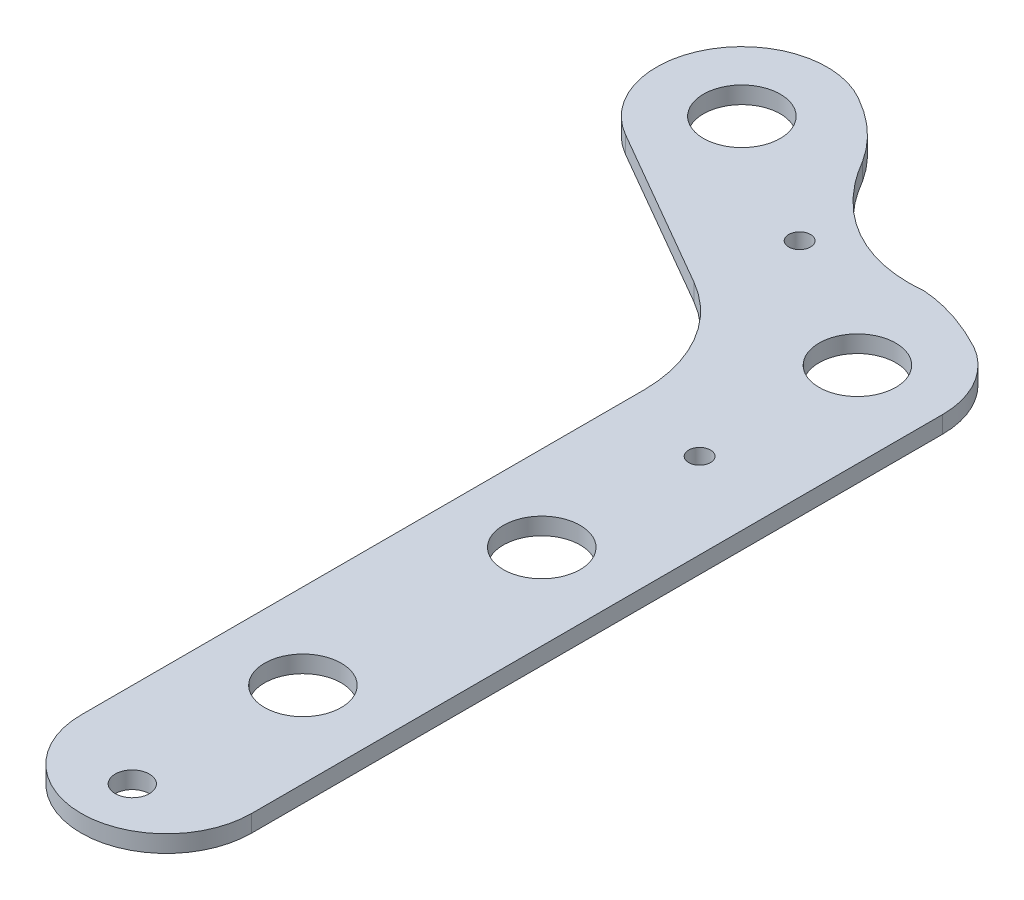
SolidWorks part; units mm, degrees
material "PC High Viscosity"
ref_plane "Front Plane" through (0, 0, 0) normal (0, 0, 1) x (1, 0, 0)
ref_plane "Top Plane" through (0, 0, 0) normal (0, 1, 0) x (1, 0, 0)
ref_plane "Right Plane" through (0, 0, 0) normal (1, 0, 0) x (0, 0, -1)
sketch "Sketch2" plane through (0, 0, 0) normal (0, 1, 0) x (1, 0, 0)
  line L0 (0, 117.475) -> (0, -88.9) construction
  line L1 (0, 117.475) -> (-101.7363, 176.2125) construction
  line L2 (31.75, -78.393) -> (31.75, 117.475)
  line L3 (-31.75, -18.2729) -> (-31.75, 69.8147)
  line L4 (-57.15, 113.8088) -> (-117.6113, 148.7162)
  line L5 (-59.6527, 249.1035) -> (-151.7481, 89.5896) construction
  line L6 (-85.8613, 203.7088) -> (15.875, 144.9713) construction
  line L7 (59.941, 221.2959) -> (-45.6102, 38.4758) construction
  line L8 (-50.8682, 146.8437) -> (-34.9932, 174.3401) construction
  line L9 (-34.9932, 174.3401) -> (22.7698, 274.3885) construction
  line L10 (-31.75, -139.7) -> (-31.75, -18.2729)
  line L11 (31.75, -78.393) -> (31.75, -139.7)
  circle A0 centre (0, 0) radius 14.2875
  circle A1 centre (0, -88.9) radius 14.2875
  circle A2 centre (0, 117.475) radius 14.2875
  circle A3 centre (-101.7363, 176.2125) radius 14.2875
  arc A5 (-117.6113, 148.7162) -> (-85.8613, 203.7088) centre (-101.7363, 176.2125) cw
  arc A6 (31.75, 117.475) -> (15.875, 144.9713) centre (0, 117.475) ccw
  arc A7 (-31.75, 69.8147) -> (-57.15, 113.8088) centre (-82.55, 69.8147) ccw
  circle A8 centre (-101.7363, 176.2125) radius 50.8 construction
  circle A9 centre (0, 117.475) radius 50.8 construction
  circle A10 centre (0, 0) radius 50.8 construction
  arc A12 (31.75, -139.7) -> (-31.75, -139.7) centre (0, -139.7) cw
  circle A14 centre (-50.8682, 146.8437) radius 4.064
  circle A15 centre (0, 58.7375) radius 4.064
  circle A16 centre (0, -152.4) radius 6.35
  spline S0 degree 2 poles (-85.8613, 203.7088) (-72.3863, 196.1044) (-64.7835, 184.2072) knots 0 0 0 1 1 1
  spline S1 degree 2 poles (-11.4264, 153.8358) (1.2245, 152.856) (15.875, 144.9713) knots 0 0 0 1 1 1
  spline S2 degree 3 poles (-64.7835, 184.2072) (-52.4235, 162.7716) (-33.1837, 151.6277) (-11.4264, 153.8358) knots 0 0 0 0 1 1 1 1
  dimension "D2" = 88.9
  dimension "1.125" = 28.575
  dimension "D6" = 31.75
  dimension "D7" = 101.6
  dimension "D8" = 50.8
  dimension "D9" = 50.8
  dimension "D10" = 12.7
  dimension "D11" = 61.3955
  dimension "D12" = 12.7
  dimension "D3" = 31.75
  dimension "D13" = 8.128
  dimension "D4" = 117.475
  dimension "D5" = 117.475
  dimension "0.5" = 11.9476
  dimension "D14" = 58.7375
  dimension "D15" = 63.5
extrude "Boss-Extrude1" add sketch "Sketch2" along normal blind 6.35
